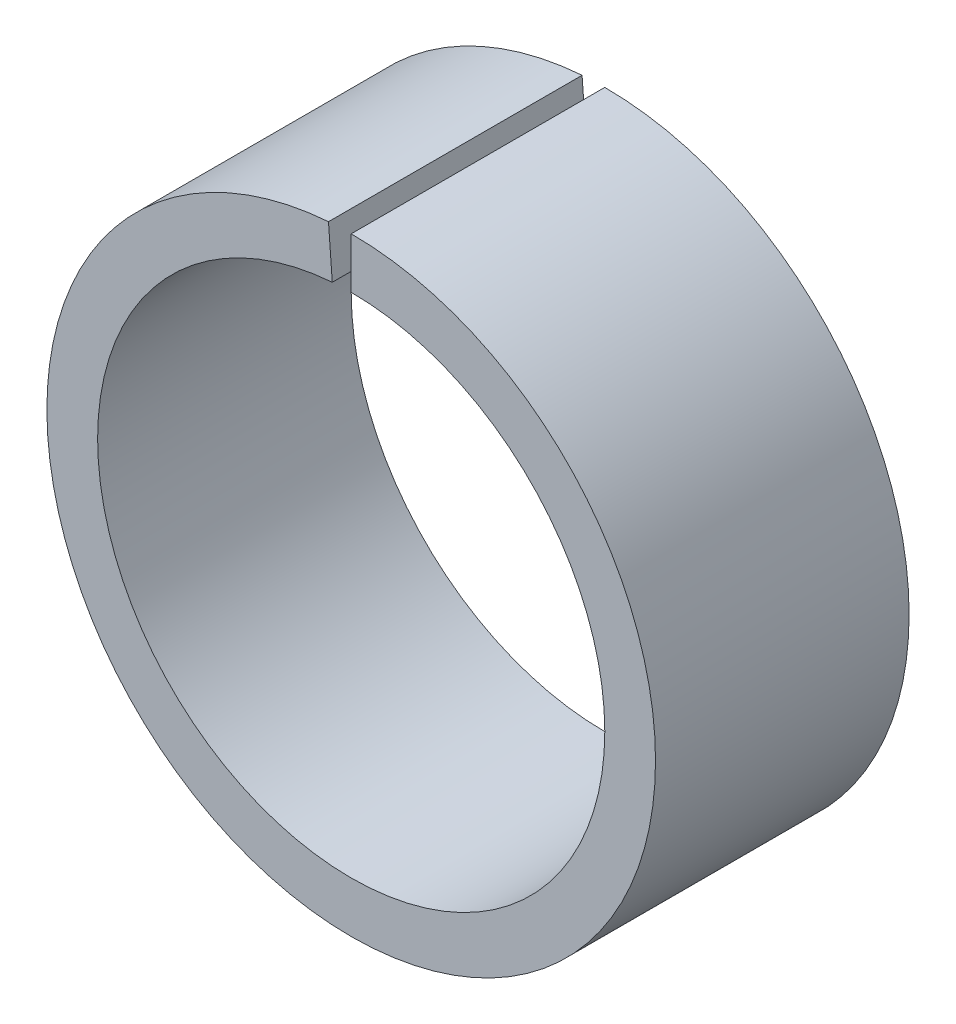
SolidWorks part; units mm, degrees
ref_plane "前视基准面" through (0, 0, 0) normal (0, 0, 1) x (1, 0, 0)
ref_plane "上视基准面" through (0, 0, 0) normal (0, 1, 0) x (1, 0, 0)
ref_plane "右视基准面" through (0, 0, 0) normal (1, 0, 0) x (0, 0, -1)
sketch "草图1" plane through (0, 0, 0) normal (0, 0, 1) x (1, 0, 0)
  circle A0 centre (0, 0) radius 6
  circle A1 centre (0, 0) radius 5
  dimension "D1" = 10
  dimension "D2" = 12
extrude "凸台-拉伸1" add sketch "草图1" along normal blind 5
sketch "草图2" plane through (0, 0, 5) normal (0, 0, 1) x (1, 0, 0)
  line L0 (0, 0) -> (0, 10.7779)
  line L1 (0, 10.7779) -> (-0.8065, 10.7779)
  line L2 (-0.8065, 10.7779) -> (0, 0)
extrude "切除-拉伸1" cut sketch "草图2" against normal blind 10
